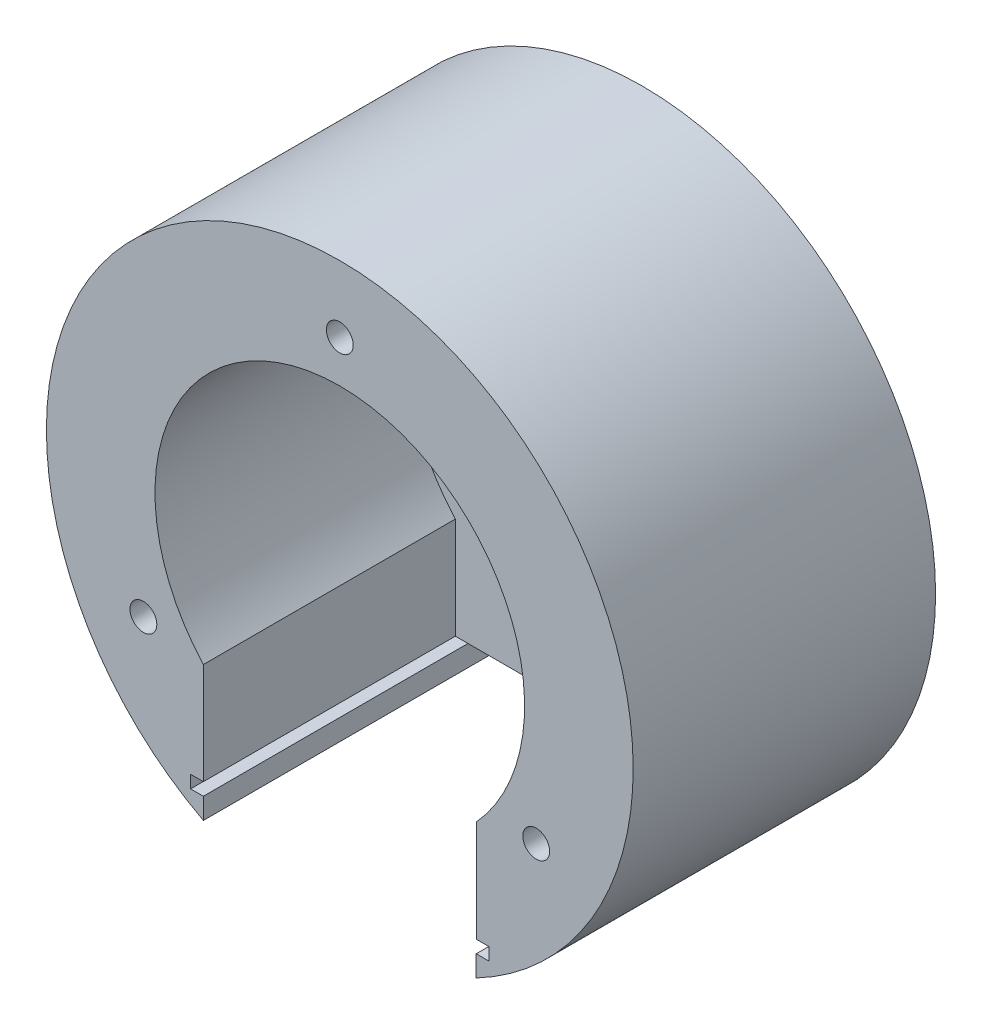
SolidWorks part; units mm, degrees
ref_plane "Front Plane" through (0, 0, 0) normal (0, 0, 1) x (1, 0, 0)
ref_plane "Top Plane" through (0, 0, 0) normal (0, 1, 0) x (1, 0, 0)
ref_plane "Right Plane" through (0, 0, 0) normal (1, 0, 0) x (0, 0, -1)
sketch "Sketch2" plane through (0, 0, 0) normal (0, 0, 1) x (1, 0, 0)
  circle A0 centre (0, 0) radius 17.4625
extrude "Boss-Extrude1" add sketch "Sketch2" along normal blind 18
sketch "Sketch13" plane through (0, 0, 18) normal (0, 0, 1) x (1, 0, 0)
  circle A0 centre (0, 13.5) radius 0.8
  circle A2 centre (11.6913, -6.75) radius 0.8
  circle A3 centre (-11.6913, -6.75) radius 0.8
  point P9 (0, 0)
  dimension "D1" = 3
  dimension "D2" = 13.5
extrude "Cut-Extrude6" cut sketch "Sketch13" against normal blind 10
sketch "Sketch16" plane through (0, 0, 18) normal (0, 0, 1) x (1, 0, 0)
  circle A0 centre (0, 0) radius 11
extrude "Cut-Extrude9" cut sketch "Sketch16" against normal blind 15
sketch "Sketch20" plane through (5.9573, 0, -11.0843) normal (0, 1, 0) x (0, 0, 1)
  line L0 (16.5293, -11.0218) -> (16.5293, -6.9068)
  line L1 (23.6393, -11.0218) -> (23.6393, -0.8118)
  line L2 (14.9293, -6.9068) -> (14.9293, -4.9268)
  line L3 (14.9293, -6.9068) -> (16.5293, -6.9068)
  line L4 (14.9293, -4.9268) -> (16.5293, -4.9268)
  line L5 (16.5293, -4.9268) -> (16.5293, -0.8118)
  line L6 (16.5293, -0.8118) -> (18.0543, -0.8118)
  line L7 (18.0543, -0.8118) -> (18.0543, 1.0282)
  line L8 (22.1143, -0.8118) -> (22.1143, 1.0282)
  line L9 (18.0543, 1.0282) -> (22.1143, 1.0282)
  line L10 (18.0543, -12.8618) -> (18.0543, -11.0218)
  line L11 (18.0543, -12.8618) -> (22.1143, -12.8618)
  line L12 (22.1143, -12.8618) -> (22.1143, -11.0218)
  line L13 (23.6393, -0.8118) -> (22.1143, -0.8118)
  line L14 (23.6393, -11.0218) -> (22.1143, -11.0218)
  line L15 (16.5293, -11.0218) -> (18.0543, -11.0218)
  line L16 (29.0843, -9.7935) -> (23.6393, -9.7935) construction
  line L18 (29.0843, -23.4198) -> (29.0843, 11.5052) construction
  line L19 (16.5293, -9.7935) -> (11.0843, -9.7935) construction
  line L20 (11.0843, 11.5052) -> (11.0843, -23.4198) construction
  dimension "D2" = 4.06
  dimension "D3" = 10.21
  dimension "D4" = 13.89
  dimension "D5" = 1.98
  dimension "D6" = 8.71
  dimension "D7" = 7.11
extrude "Cut-Extrude11" cut sketch "Sketch20" against normal blind 22
sketch "Sketch21" plane through (0, 0, 18) normal (0, 0, 1) x (1, 0, 0)
  line L1 (-8.125, -15.46) -> (8.125, -15.46)
  line L2 (-8.125, -15.46) -> (-8.125, -18.2444)
  line L3 (-8.125, -18.2444) -> (8.125, -18.2444)
  line L4 (8.125, -15.46) -> (8.125, -18.2444)
  dimension "D1" = 16.25
  dimension "D2" = 8.125
  dimension "D3" = 15.46
extrude "Cut-Extrude12" cut sketch "Sketch21" against normal through all
sketch "Sketch24" plane through (0, 0, 18) normal (0, 0, 1) x (1, 0, 0)
  line L0 (-8.1196, -6.7586) -> (8.1304, -6.7586)
  line L1 (-8.1196, -6.7586) -> (-8.1196, -13.46)
  line L2 (-8.1196, -13.46) -> (8.1304, -13.46)
  line L3 (8.1304, -6.7586) -> (8.1304, -13.46)
  dimension "D1" = 16.25
extrude "Cut-Extrude13" cut sketch "Sketch24" against normal up to surface (15 mm away) up to face at (11, 0, 3)
sketch "Sketch26" plane through (0, 0, 18) normal (0, 0, 1) x (1, 0, 0)
  line L4 (-8.1196, -14.21) -> (-8.1196, -15.46)
  line L5 (-8.1196, -15.46) -> (8.1196, -15.46)
  line L6 (8.1196, -15.46) -> (8.1196, -14.21)
  line L11 (8.1304, -13.46) -> (-8.1196, -13.46)
  line L12 (-8.1196, -13.46) -> (-8.8796, -13.46)
  line L13 (-8.8796, -13.46) -> (-8.8796, -14.21)
  line L14 (-8.8796, -14.21) -> (-8.1196, -14.21)
  line L15 (8.1304, -13.46) -> (8.8904, -13.46)
  line L16 (8.8904, -13.46) -> (8.8904, -14.21)
  line L17 (8.8904, -14.21) -> (8.1196, -14.21)
  dimension "D1" = 0.76
  dimension "D2" = 0.75
  dimension "D3" = 0.76
  dimension "D4" = 0.75
extrude "Cut-Extrude14" cut sketch "Sketch26" against normal blind 17
